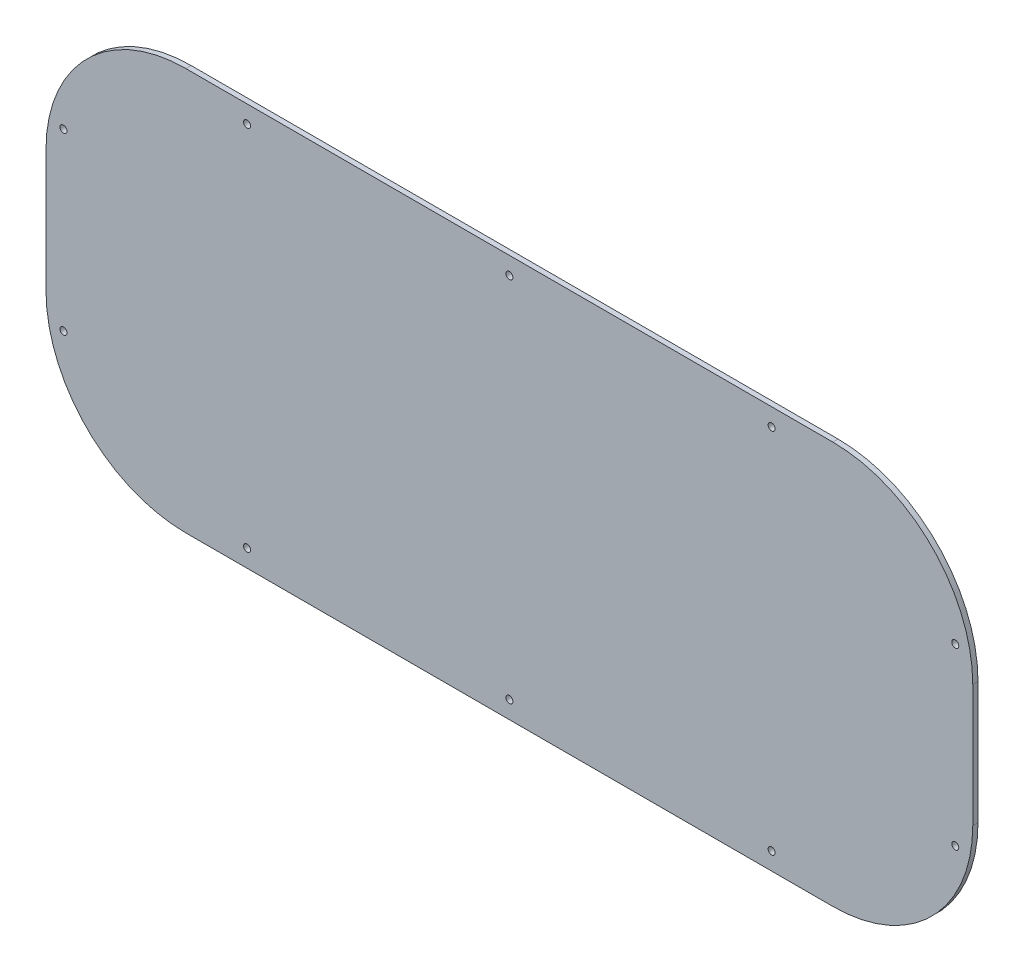
SolidWorks part; units mm, degrees
ref_plane "前视基准面" through (0, 0, 0) normal (0, 0, 1) x (1, 0, 0)
ref_plane "上视基准面" through (0, 0, 0) normal (0, 1, 0) x (1, 0, 0)
ref_plane "右视基准面" through (0, 0, 0) normal (1, 0, 0) x (0, 0, -1)
sketch "草图1" plane through (0, 0, 0) normal (0, 0, 1) x (1, 0, 0)
  line L1 (-265, 115) -> (265, 115)
  line L2 (-265, 115) -> (-265, -115)
  line L3 (-265, -115) -> (265, -115)
  line L4 (265, 115) -> (265, -115)
  line L5 (-265, 115) -> (265, -115) construction
  line L6 (-265, -115) -> (265, 115) construction
  point P0 (0, 0)
  dimension "D1" = 230
  dimension "D2" = 530
extrude "凸台-拉伸1" add sketch "草图1" along normal blind 3
fillet "圆角1" radius 80 4 edges at (265, 115, 1.5) (-265, 115, 1.5) (-265, -115, 1.5) (265, -115, 1.5)
sketch "草图2" plane through (0, 0, 3) normal (0, 0, 1) x (1, 0, 0)
  circle A0 centre (-255, -50) radius 2
  circle A1 centre (-255, 50) radius 2
  circle A2 centre (-150, -105) radius 2
  circle A3 centre (0, -105) radius 2
  circle A4 centre (150, -105) radius 2
  circle A5 centre (255, -50) radius 2
  circle A6 centre (255, 50) radius 2
  circle A7 centre (150, 105) radius 2
  circle A8 centre (0, 105) radius 2
  circle A9 centre (-150, 105) radius 2
  dimension "D1" = 4
extrude "切除-拉伸1" cut sketch "草图2" against normal blind 10
